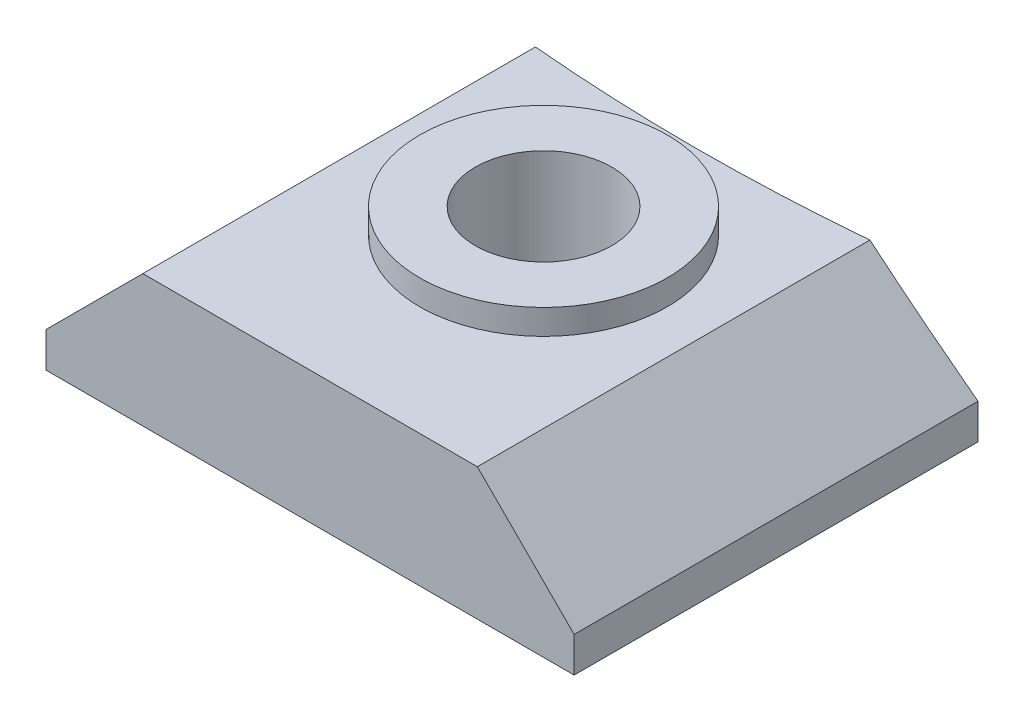
SolidWorks part; units mm, degrees
material "ABS"
ref_plane "Front" through (0, 0, 0) normal (0, 0, 1) x (1, 0, 0)
ref_plane "Top" through (0, 0, 0) normal (0, 1, 0) x (1, 0, 0)
ref_plane "Right" through (0, 0, 0) normal (1, 0, 0) x (0, 0, -1)
sketch "Sketch1" plane through (0, 0, 0) normal (0, 0, 1) x (1, 0, 0)
  line L0 (-12, 0) -> (12, 0)
  line L1 (12, 0) -> (12, 1.6)
  line L2 (12, 1.6) -> (7.6, 6)
  line L3 (7.6, 6) -> (-7.6, 6)
  line L4 (-7.6, 6) -> (-12, 1.6)
  line L5 (-12, 1.6) -> (-12, 0)
  point P2 (0, 0)
  point P8 (0, 6)
  dimension "D1" = 45
  dimension "D2" = 24
  dimension "D3" = 6
  dimension "D4" = 1.6
extrude "Boss-Extrude1" add sketch "Sketch1" along normal blind 22
sketch "Sketch2" plane through (0, 6, 0) normal (0, 1, 0) x (1, 0, 0)
  circle A0 centre (0, -11.3911) radius 5.625
  dimension "D1" = 11.25
extrude "Boss-Extrude2" add sketch "Sketch2" along normal blind 1.14
sketch "Sketch3" plane through (0, 7.14, 0) normal (0, 1, 0) x (1, 0, 0)
  circle A0 centre (0, -11.3911) radius 3.1
  dimension "D1" = 6.2
extrude "Cut-Extrude3" cut sketch "Sketch3" against normal through all
sketch "Sketch4" plane through (0, 6, 0) normal (0, 1, 0) x (1, 0, 0)
  line L0 (-12, -22) -> (-12, 0) construction
  line L1 (12, -22) -> (12, 0) construction
  line L2 (-12, -3.6487) -> (-12, 0)
  line L3 (-12, 0) -> (12, 0)
  line L4 (12, 0) -> (12, -3.6487)
  arc A0 (-12, -3.6487) -> (12, -3.6487) centre (0, 80.5) ccw
  point P3 (0, -4.5)
  dimension "D2" = 85
  dimension "D1" = 4.5
extrude "Cut-Extrude4" cut sketch "Sketch4" against normal through all
